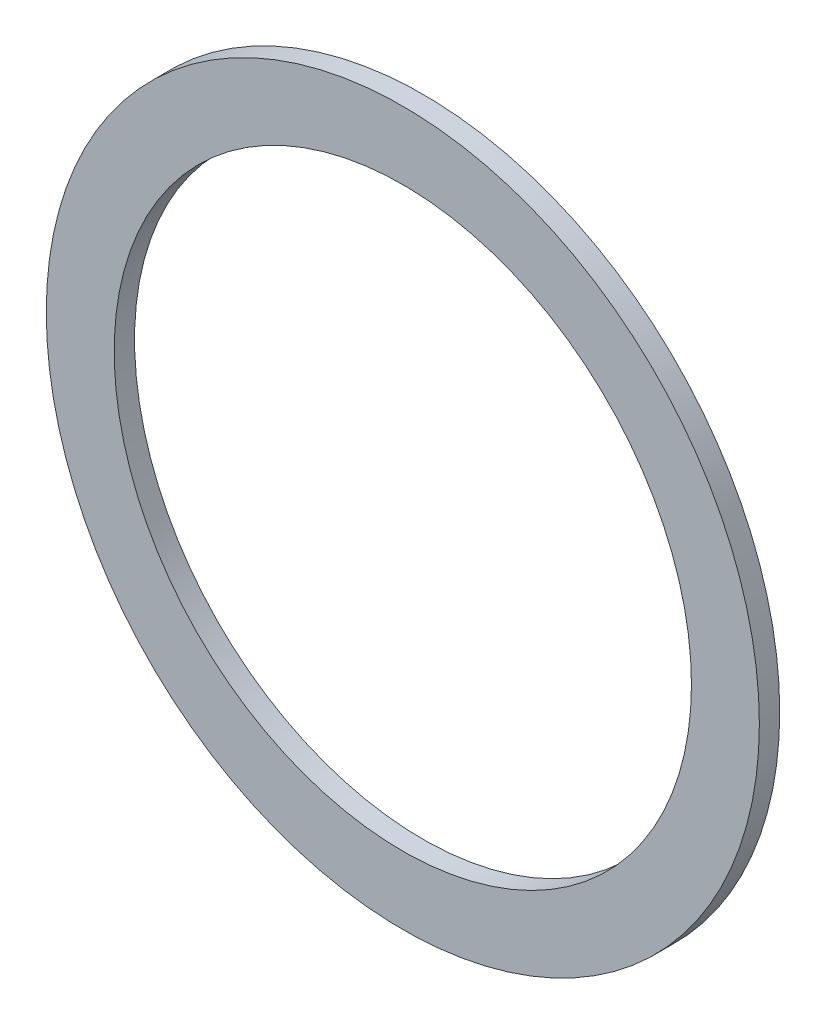
SolidWorks part; units mm, degrees
ref_plane "前基準面" through (0, 0, 0) normal (0, 0, 1) x (1, 0, 0)
ref_plane "上基準面" through (0, 0, 0) normal (0, 1, 0) x (1, 0, 0)
ref_plane "右基準面" through (0, 0, 0) normal (1, 0, 0) x (0, 0, -1)
sketch "草圖1" plane through (0, 0, 0) normal (0, 0, 1) x (1, 0, 0)
  circle A0 centre (0, 0) radius 0.85
  circle A1 centre (0, 0) radius 1.05
extrude "填料-伸長1" add sketch "草圖1" along normal blind 0.06
sketch "草圖3" plane through (0, 0, 0) normal (0, 0, -1) x (-1, 0, 0)
  line L0 (0, 0) -> (0, 1.0678) construction
  line L1 (0, 0) -> (1.4527, 0) construction
  point P3 (0, 0.94)
  dimension "D1" = 0.94
